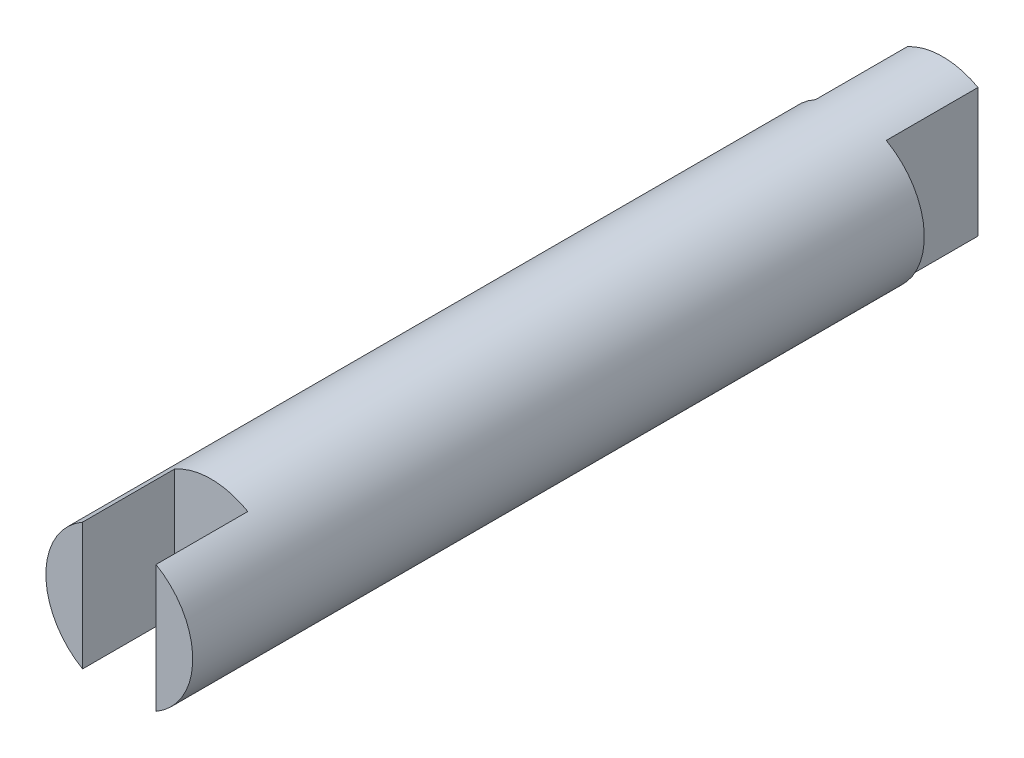
SolidWorks part; units mm, degrees
ref_plane "Front Plane" through (0, 0, 0) normal (0, 0, 1) x (1, 0, 0)
ref_plane "Top Plane" through (0, 0, 0) normal (0, 1, 0) x (1, 0, 0)
ref_plane "Right Plane" through (0, 0, 0) normal (1, 0, 0) x (0, 0, -1)
sketch "Sketch1" plane through (0, 0, 0) normal (0, 0, 1) x (1, 0, 0)
  circle A0 centre (0, 0) radius 4
  dimension "D1" = 8
extrude "Boss-Extrude1" add sketch "Sketch1" against normal blind 39.85
sketch "Sketch2" plane through (0, 0, 0) normal (0, 0, 1) x (1, 0, 0)
  line L0 (-2, 3.4641) -> (-2, -3.4641)
  line L1 (2, 3.4641) -> (2, -3.4641)
  circle A0 centre (0, 0) radius 4 construction
  arc A1 (-2, 3.4641) -> (-2, -3.4641) centre (0, 0) ccw
  arc A2 (2, 3.4641) -> (-2, 3.4641) centre (0, 0) ccw construction
  arc A3 (-2, -3.4641) -> (2, -3.4641) centre (0, 0) ccw construction
  arc A4 (2, -3.4641) -> (2, 3.4641) centre (0, 0) ccw
  dimension "D1" = 2
  dimension "2" = 2
extrude "Boss-Extrude2" add sketch "Sketch2" along normal blind 5
ref_plane "Plane1" through (0, 0, -40) normal (0, 0, 1) x (1, 0, 0)
sketch "Sketch3" plane through (0, 0, -39.85) normal (0, 0, -1) x (-1, 0, 0)
  line L0 (-1.925, 3.5063) -> (-1.925, -3.5063)
  line L1 (1.925, 3.5063) -> (1.925, -3.5063)
  arc A0 (1.925, 3.5063) -> (-1.925, 3.5063) centre (0, 0) ccw construction
  circle A1 centre (0, 0) radius 4
  arc A2 (-1.925, 3.5063) -> (-1.925, -3.5063) centre (0, 0) ccw
  arc A3 (-1.925, -3.5063) -> (1.925, -3.5063) centre (0, 0) ccw construction
  arc A4 (1.925, -3.5063) -> (1.925, 3.5063) centre (0, 0) ccw
  dimension "D2" = 1.925
  dimension "D3" = 1.925
  dimension "D1" = 0
extrude "Cut-Extrude1" cut sketch "Sketch3" against normal blind 5
